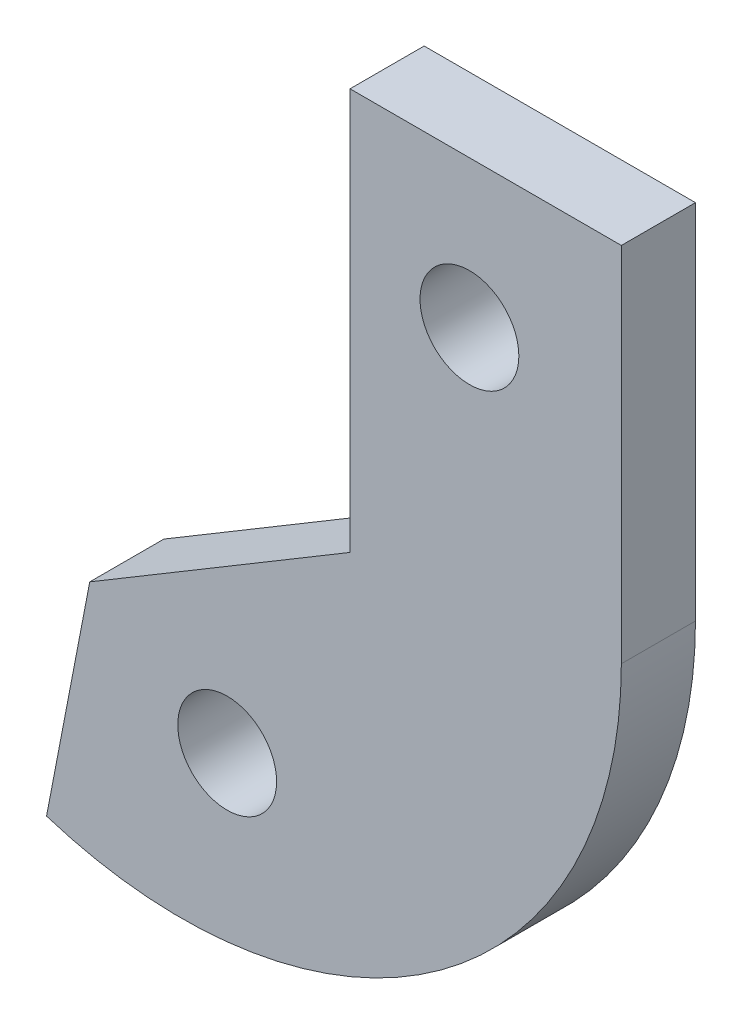
SolidWorks part; units mm, degrees
ref_plane "Płaszczyzna przednia" through (0, 0, 0) normal (0, 0, 1) x (1, 0, 0)
ref_plane "Płaszczyzna górna" through (0, 0, 0) normal (0, 1, 0) x (1, 0, 0)
ref_plane "Płaszczyzna prawa" through (0, 0, 0) normal (1, 0, 0) x (0, 0, -1)
sketch "Sketch2" plane through (0, 0, 0) normal (0, 0, 1) x (-1, 0, 0)
  line L3 (-9.018, -7.3323) -> (-20, -7.3323)
  line L4 (-20, 7.3323) -> (-20, -7.3323)
  line L6 (-9.018, 8.9202) -> (-9.018, -7.3323)
  line L8 (-9.018, 8.9202) -> (1.5184, 15.2204)
  line L9 (3.2672, 24.3059) -> (0, 7.3323) construction
  line L10 (1.5184, 15.2204) -> (3.2672, 24.3059)
  circle A2 centre (-13.851, -1.3792) radius 2
  arc A3 (-20, 7.3323) -> (3.2672, 24.3059) centre (-2.1752, 7.3323) cw
  circle A6 centre (-4.0453, 18.4434) radius 2
  dimension "D2" = 4
  dimension "D3" = 4
  dimension "D1" = 17.8248
  dimension "D4" = 14.6646
extrude "Boss-Extrude1" add sketch "Sketch2" along normal blind 3
